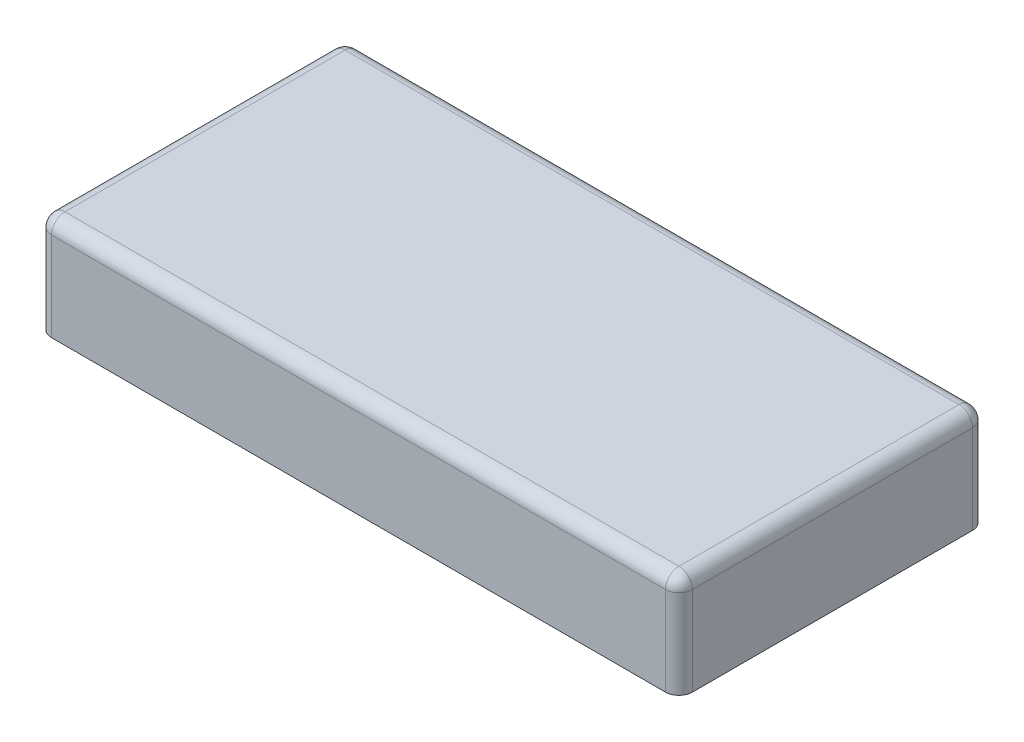
SolidWorks part; units mm, degrees
ref_plane "Спереди" through (0, 0, 0) normal (0, 0, 1) x (1, 0, 0)
ref_plane "Сверху" through (0, 0, 0) normal (0, 1, 0) x (1, 0, 0)
ref_plane "Справа" through (0, 0, 0) normal (1, 0, 0) x (0, 0, -1)
sketch "Эскиз2" plane through (0, 1.2711, 0) normal (0, 1, 0) x (1, 0, 0)
  line L0 (45.2, 0) -> (0, 0) construction
  line L1 (0, 0) -> (45.2, 0)
  line L2 (0, 0) -> (0, 20.4)
  line L3 (0, 20.4) -> (45.2, 20.4)
  line L4 (45.2, 0) -> (45.2, 20.4)
  line L5 (-0.2, -0.2) -> (45.4, -0.2)
  line L6 (-0.2, -0.2) -> (-0.2, 20.6)
  line L7 (-0.2, 20.6) -> (45.4, 20.6)
  line L8 (45.4, -0.2) -> (45.4, 20.6)
  line L9 (46.4, -1.2) -> (46.4, 21.6)
  line L10 (-1.2, 21.6) -> (46.4, 21.6)
  line L11 (-1.2, -1.2) -> (-1.2, 21.6)
  line L12 (-1.2, -1.2) -> (46.4, -1.2)
  dimension "D1" = 0.2
  dimension "D2" = 0.2
  dimension "D3" = 0.2
  dimension "D4" = 0.2
  dimension "D5" = 1
extrude "Бобышка-Вытянуть1" add sketch "Эскиз2" against normal blind 1.6 contours L9 L10 L11 L12 | L6 L5 L8 L7
sketch "Эскиз3" plane through (0, 1.2711, 0) normal (0, 1, 0) x (1, 0, 0)
  line L1 (-1.2, -1.2) -> (46.4, -1.2)
  line L2 (-1.2, -1.2) -> (-1.2, 21.6)
  line L3 (-1.2, 21.6) -> (46.4, 21.6)
  line L4 (46.4, -1.2) -> (46.4, 21.6)
  line L5 (45.4, 20.6) -> (-0.2, 20.6)
  line L6 (45.4, 20.6) -> (45.4, -0.2)
  line L7 (45.4, -0.2) -> (-0.2, -0.2)
  line L8 (-0.2, 20.6) -> (-0.2, -0.2)
extrude "Бобышка-Вытянуть2" add sketch "Эскиз3" along normal blind 2
sketch "Эскиз4" plane through (0, 3.2711, 0) normal (0, 1, 0) x (1, 0, 0)
  line L1 (46.4, -1.2) -> (-1.2, -1.2)
  line L2 (46.4, -1.2) -> (46.4, 21.6)
  line L3 (46.4, 21.6) -> (-1.2, 21.6)
  line L4 (-1.2, -1.2) -> (-1.2, 21.6)
extrude "Бобышка-Вытянуть3" add sketch "Эскиз4" along normal blind 1
sketch "Эскиз5" plane through (0, -0.3289, 0) normal (0, -1, 0) x (1, 0, 0)
  line L1 (-1.2, -21.6) -> (46.4, -21.6)
  line L2 (-1.2, -21.6) -> (-1.2, 1.2)
  line L3 (-1.2, 1.2) -> (46.4, 1.2)
  line L4 (46.4, -21.6) -> (46.4, 1.2)
  line L6 (-0.2, 0.2) -> (45.4, 0.2)
  line L7 (-0.2, 0.2) -> (-0.2, -20.6)
  line L8 (-0.2, -20.6) -> (45.4, -20.6)
  line L9 (45.4, 0.2) -> (45.4, -20.6)
extrude "Бобышка-Вытянуть4" add sketch "Эскиз5" along normal blind 3
sketch "Эскиз6" plane through (0, 0, -21.6) normal (0, 0, -1) x (-1, 0, 0)
  line L0 (1.2, -3.3289) -> (-46.4, -3.3289) construction
  line L1 (-25.5999, -3.3289) -> (-16.9999, -3.3289)
  line L2 (-25.5999, -3.3289) -> (-25.5999, -0.7)
  line L3 (-25.5999, -0.7) -> (-16.9999, -0.7)
  line L4 (-16.9999, -3.3289) -> (-16.9999, -0.7)
  line L5 (-25.2999, -2.5) -> (-25.2999, -1) construction
  line L6 (-17.2999, -1) -> (-17.2999, -2.5) construction
  line L7 (-15.1001, -0.2) -> (-2.7001, -0.2) construction
  line L8 (-15.4001, -3.3289) -> (-2.4001, -3.3289)
  line L9 (-15.4001, -3.3289) -> (-15.4001, 0.1)
  line L10 (-15.4001, 0.1) -> (-2.4001, 0.1)
  line L11 (-2.4001, -3.3289) -> (-2.4001, 0.1)
  line L12 (-42.1499, -0.2) -> (-32.2499, -0.2) construction
  line L13 (-42.4499, -3.3289) -> (-31.9499, -3.3289)
  line L14 (-42.4499, -3.3289) -> (-42.4499, 0.1)
  line L15 (-42.4499, 0.1) -> (-31.9499, 0.1)
  line L16 (-31.9499, -3.3289) -> (-31.9499, 0.1)
  dimension "D1" = 0.3
  dimension "D2" = 0.3
  dimension "D3" = 0.3
  dimension "D4" = 0.3
  dimension "D5" = 0.3
  dimension "D6" = 0.3
  dimension "D7" = 0.3
  dimension "D8" = 0.3
  dimension "D9" = 0.3
extrude "Вырез-Вытянуть1" cut sketch "Эскиз6" against normal up to surface (1 mm away) up to face at (22.6, -0.0289, -20.6)
sketch "Эскиз7" plane through (0, -3.3289, 0) normal (0, -1, 0) x (1, 0, 0)
  line L0 (-1.2, -21.6) -> (-0.2, -20.6) construction
  line L1 (-0.2, 0.2) -> (45.4, 0.2)
  line L2 (-0.2, 0.2) -> (-0.2, -20.6)
  line L3 (-0.2, -20.6) -> (2.4001, -20.6)
  line L4 (45.4, 0.2) -> (45.4, -20.6)
  line L5 (45.4, 0.2) -> (46.4, 1.2) construction
  line L6 (2.4001, -21.1) -> (2.4001, -20.6)
  line L7 (45.9, 0.7) -> (-0.7, 0.7)
  line L8 (45.9, 0.7) -> (45.9, -21.1)
  line L9 (45.9, -21.1) -> (42.4499, -21.1)
  line L10 (-0.7, 0.7) -> (-0.7, -21.1)
  line L11 (2.4001, -20.6) -> (2.4001, -21.6) construction
  line L12 (15.4001, -21.1) -> (15.4001, -20.6)
  line L13 (15.4001, -20.6) -> (15.4001, -21.6) construction
  line L14 (16.9999, -21.1) -> (16.9999, -20.6)
  line L15 (16.9999, -20.6) -> (16.9999, -21.6) construction
  line L16 (25.5999, -21.1) -> (25.5999, -20.6)
  line L17 (25.5999, -20.6) -> (25.5999, -21.6) construction
  line L18 (31.9499, -21.1) -> (31.9499, -20.6)
  line L19 (31.9499, -20.6) -> (31.9499, -21.6) construction
  line L20 (42.4499, -21.1) -> (42.4499, -20.6)
  line L21 (42.4499, -20.6) -> (42.4499, -21.6) construction
  line L22 (2.4001, -21.1) -> (-0.7, -21.1)
  line L23 (15.4001, -20.6) -> (16.9999, -20.6)
  line L24 (16.9999, -21.1) -> (15.4001, -21.1)
  line L25 (25.5999, -20.6) -> (31.9499, -20.6)
  line L26 (31.9499, -21.1) -> (25.5999, -21.1)
  line L27 (42.4499, -20.6) -> (45.4, -20.6)
extrude "Вырез-Вытянуть2" cut sketch "Эскиз7" against normal blind 1
fillet "Скругление1" radius 1 8 edges at (22.6, 4.2711, 1.2) (-1.2, 4.2711, -10.2) (22.6, 4.2711, -21.6) (46.4, 4.2711, -10.2) (46.4, 0.4711, -21.6) (46.4, 0.4711, 1.2) (-1.2, 0.4711, 1.2) (-1.2, 0.4711, -21.6)
